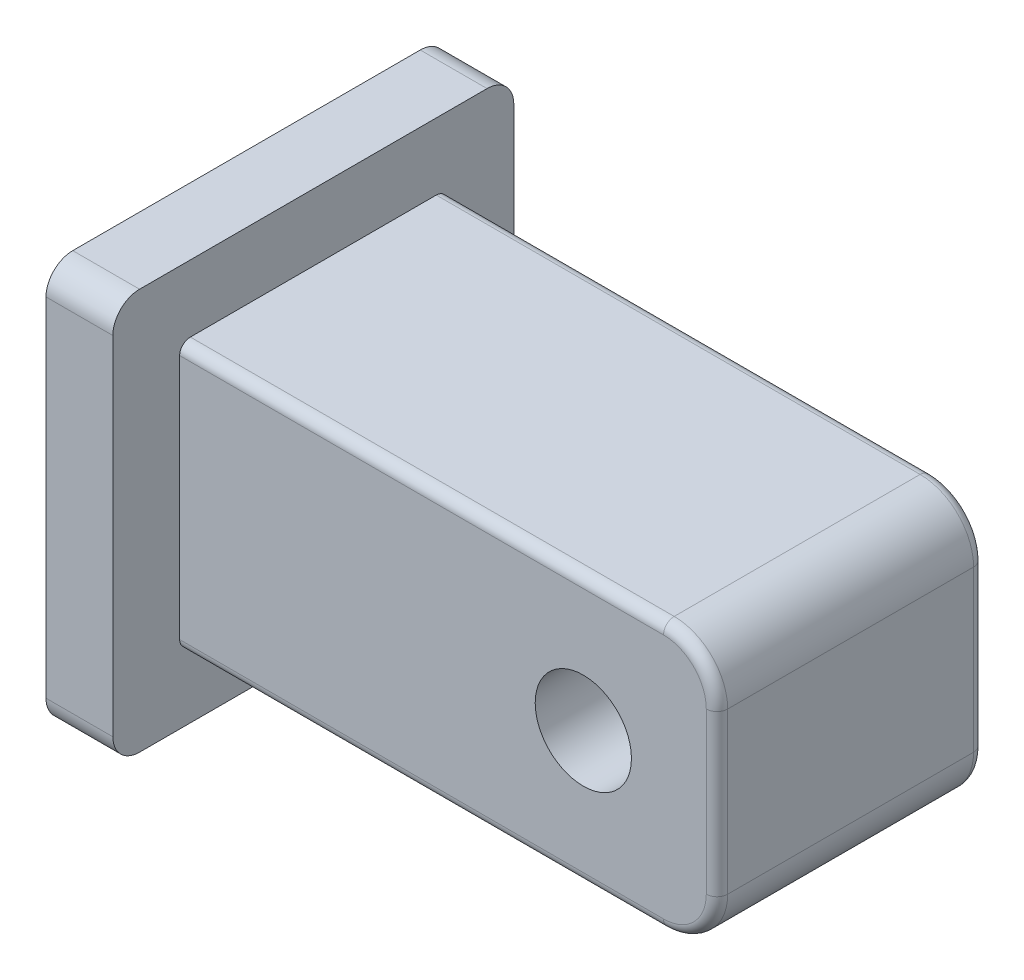
SolidWorks part; units mm, degrees
ref_plane "Front Plane" through (0, 0, 0) normal (0, 0, 1) x (1, 0, 0)
ref_plane "Top Plane" through (0, 0, 0) normal (0, 1, 0) x (1, 0, 0)
ref_plane "Right Plane" through (0, 0, 0) normal (1, 0, 0) x (0, 0, -1)
sketch "Sketch2" plane through (0, 0, 0) normal (0, 0, 1) x (1, 0, 0)
  line L1 (0, 0) -> (-28.702, 0)
  line L2 (0, 0) -> (0, -12.7)
  line L3 (0, -12.7) -> (-28.702, -12.7)
  line L4 (-28.702, 0) -> (-28.702, -12.7)
  dimension "D1" = 28.702
  dimension "D2" = 12.7
extrude "Boss-Extrude1" add sketch "Sketch2" along normal blind 12.7
sketch "Sketch3" plane through (0, 0, 12.7) normal (0, 0, 1) x (1, 0, 0)
  line L0 (0, -12.7) -> (0, 0) construction
  line L1 (-28.702, -12.7) -> (0, -12.7) construction
  circle A0 centre (-6.35, -6.35) radius 2.286
  dimension "D1" = 4.572
  dimension "D2" = 6.35
  dimension "D3" = 6.35
extrude "Cut-Extrude1" cut sketch "Sketch3" against normal through all both and the other way through all
fillet "Fillet1" radius 2.54 2 edges at (0, -12.7, 6.35) (0, 0, 6.35)
sketch "Sketch4" plane through (-28.702, 0, 0) normal (-1, 0, 0) x (0, 0, 1)
  line L1 (-3.175, 3.175) -> (15.875, 3.175)
  line L2 (-3.175, 3.175) -> (-3.175, -15.875)
  line L3 (-3.175, -15.875) -> (15.875, -15.875)
  line L4 (15.875, 3.175) -> (15.875, -15.875)
  line L5 (-3.175, 3.175) -> (15.875, -15.875) construction
  line L6 (-3.175, -15.875) -> (15.875, 3.175) construction
  line L7 (0, 0) -> (0, -12.7) construction
  line L8 (12.7, -12.7) -> (0, -12.7) construction
  line L9 (12.7, 0) -> (12.7, -12.7) construction
  point P0 (6.35, -6.35)
  dimension "D1" = 3.175
  dimension "D2" = 3.175
  dimension "D3" = 3.175
extrude "Boss-Extrude2" add sketch "Sketch4" against normal blind 3.175
fillet "Fillet2" radius 0.508 10 edges at (-14.0335, -12.7, 0) (-0.7439, -11.9561, 0) (0, -6.35, 0) (-0.7439, -0.7439, 0) (-14.0335, -12.7, 12.7) (-0.7439, -11.9561, 12.7) (0, -6.35, 12.7) (-0.7439, -0.7439, 12.7) (-14.0335, 0, 0) (-14.0335, 0, 12.7)
fillet "Fillet3" radius 1.27 4 edges at (-27.1145, -15.875, -3.175) (-27.1145, -15.875, 15.875) (-27.1145, 3.175, -3.175) (-27.1145, 3.175, 15.875)
